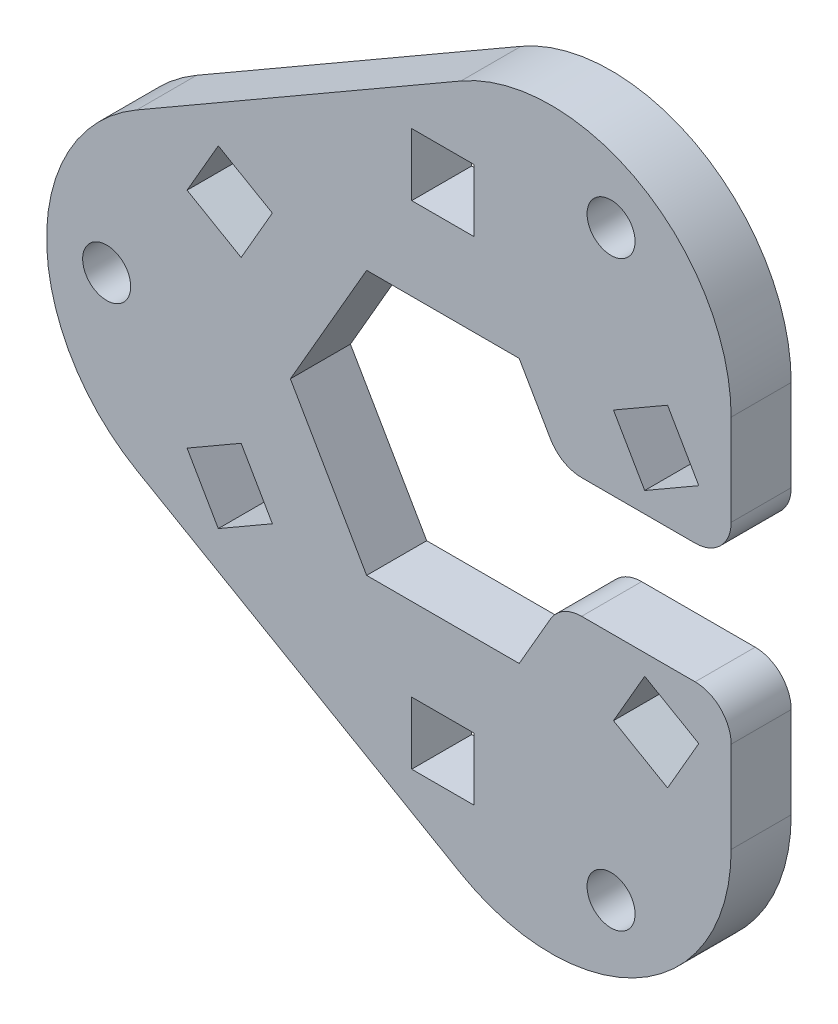
SolidWorks part; units mm, degrees
ref_plane "Front Plane" through (0, 0, 0) normal (0, 0, 1) x (1, 0, 0)
ref_plane "Top Plane" through (0, 0, 0) normal (0, 1, 0) x (1, 0, 0)
ref_plane "Right Plane" through (0, 0, 0) normal (1, 0, 0) x (0, 0, -1)
sketch "Sketch1" plane through (0, 0, 0) normal (0, 0, 1) x (1, 0, 0)
  line L0 (-26, 0) -> (26, 0) construction
  line L7 (-2.6, 23.1) -> (2.6, 23.1)
  line L8 (-2.6, 23.1) -> (-2.6, 17.9)
  line L9 (-2.6, 17.9) -> (2.6, 17.9)
  line L10 (2.6, 23.1) -> (2.6, 17.9)
  line L23 (0, 26) -> (0, -26) construction
  line L24 (21.3052, 9.2983) -> (16.8019, 6.6983)
  line L25 (14.2019, 11.2017) -> (16.8019, 6.6983)
  line L26 (18.7052, 13.8017) -> (14.2019, 11.2017)
  line L27 (18.7052, 13.8017) -> (21.3052, 9.2983)
  line L28 (18.7052, -13.8017) -> (14.2019, -11.2017)
  line L29 (16.8019, -6.6983) -> (14.2019, -11.2017)
  line L30 (21.3052, -9.2983) -> (16.8019, -6.6983)
  line L31 (21.3052, -9.2983) -> (18.7052, -13.8017)
  line L32 (-2.6, -23.1) -> (-2.6, -17.9)
  line L33 (2.6, -17.9) -> (-2.6, -17.9)
  line L34 (2.6, -23.1) -> (2.6, -17.9)
  line L35 (2.6, -23.1) -> (-2.6, -23.1)
  line L36 (-21.3052, -9.2983) -> (-16.8019, -6.6983)
  line L37 (-14.2019, -11.2017) -> (-16.8019, -6.6983)
  line L38 (-18.7052, -13.8017) -> (-14.2019, -11.2017)
  line L39 (-18.7052, -13.8017) -> (-21.3052, -9.2983)
  line L40 (-18.7052, 13.8017) -> (-14.2019, 11.2017)
  line L41 (-16.8019, 6.6983) -> (-14.2019, 11.2017)
  line L42 (-21.3052, 9.2983) -> (-16.8019, 6.6983)
  line L43 (-21.3052, 9.2983) -> (-18.7052, 13.8017)
  line L44 (24, 5) -> (9.815, 5)
  line L45 (24, -5) -> (9.815, -5)
  line L46 (24, 41.5692) -> (24, -41.5692) construction
  line L47 (24, -41.5692) -> (-48, 0) construction
  line L48 (-48, 0) -> (24, 41.5692) construction
  line L49 (24, 5) -> (24, 41.5692)
  line L50 (24, 41.5692) -> (-48, 0)
  line L51 (-48, 0) -> (24, -41.5692)
  line L52 (24, -41.5692) -> (24, -5)
  line L53 (0, 0) -> (24, 41.5692) construction
  line L54 (-2.6, 20.5) -> (2.6, 20.5) construction
  line L55 (6.3509, 11) -> (9.815, 5)
  line L56 (6.3509, -11) -> (12.7017, 0) construction
  line L57 (12.7017, 0) -> (6.3509, 11) construction
  line L58 (6.3509, 11) -> (-6.3509, 11)
  line L59 (-6.3509, 11) -> (-12.7017, 0)
  line L60 (-12.7017, 0) -> (-6.3509, -11)
  line L61 (-6.3509, -11) -> (6.3509, -11)
  line L62 (9.815, -5) -> (6.3509, -11)
  circle A0 centre (0, 0) radius 13.75 construction
  circle A4 centre (14, 24.2487) radius 2
  circle A5 centre (14, -24.2487) radius 2
  circle A6 centre (-28, 0) radius 2
  circle A7 centre (0, 0) radius 11 construction
  point P40 (0, 0)
  point P48 (0, 0)
  point P50 (0, 0)
  dimension "D2" = 24
  dimension "D1" = 27.5
  dimension "D10" = 4
  dimension "D3" = 5.2
  dimension "D4" = 5.2
  dimension "D5" = 20.5
  dimension "D6" = 6
  dimension "D7" = 10
  dimension "D9" = 28
  dimension "D11" = 3
  dimension "D12" = 22
  dimension "D13" = 17.9
  dimension "D8" = 3
extrude "Boss-Extrude1" add sketch "Sketch1" along normal blind 5
fillet "Congé1" radius 15 3 edges at (24, -41.5692, 2.5) (-48, 0, 2.5) (24, 41.5692, 2.5)
fillet "Congé2" radius 3 4 edges at (24, -5, 2.5) (24, 5, 2.5) (9.815, -5, 2.5) (9.815, 5, 2.5)
sketch "Esquisse1" plane through (0, 0, 5) normal (0, 0, 1) x (1, 0, 0)
  circle A0 centre (0, 0) radius 33 construction
  arc A1 (24, 15.5885) -> (1.5, 28.5788) centre (9, 15.5885) ccw construction
